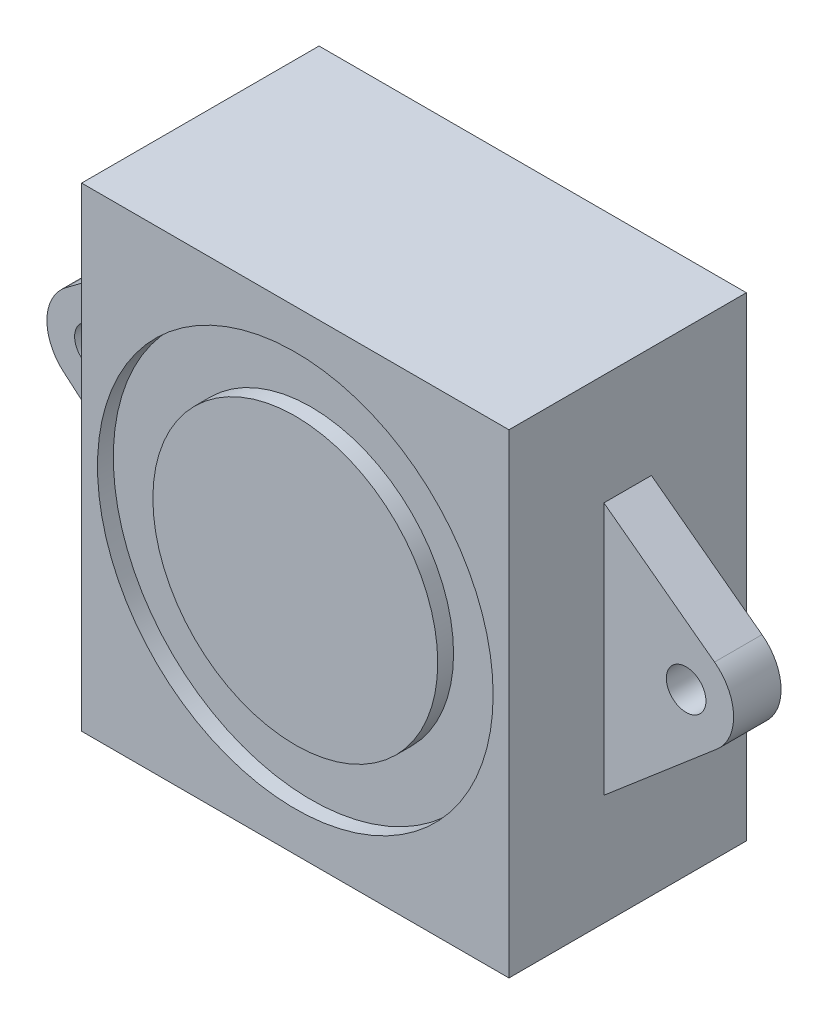
SolidWorks part; units mm, degrees
material "ABS"
ref_plane "Front Plane" through (0, 0, 0) normal (0, 0, 1) x (1, 0, 0)
ref_plane "Top Plane" through (0, 0, 0) normal (0, 1, 0) x (1, 0, 0)
ref_plane "Right Plane" through (0, 0, 0) normal (1, 0, 0) x (0, 0, -1)
sketch "Sketch1" plane through (0, 0, 0) normal (0, 0, 1) x (1, 0, 0)
  line L1 (0, 0) -> (27, 0)
  line L2 (0, 0) -> (0, 30)
  line L3 (0, 30) -> (27, 30)
  line L4 (27, 0) -> (27, 30)
  dimension "D1" = 27
  dimension "D2" = 30
extrude "Boss-Extrude1" add sketch "Sketch1" along normal blind 15
sketch "Sketch2" plane through (0, 0, 15) normal (0, 0, 1) x (1, 0, 0)
  circle A0 centre (13.5, 15) radius 9
  circle A1 centre (13.5, 15) radius 12.5
  dimension "D1" = 25
  dimension "D2" = 18
extrude "Cut-Extrude1" cut sketch "Sketch2" against normal blind 1
sketch "Sketch3" plane through (0, 0, 15) normal (0, 0, 1) x (1, 0, 0)
  line L0 (13.5, 30) -> (13.5, 17.0254)
  line L1 (27, 30) -> (0, 30) construction
  line L2 (0, 23) -> (-6.9895, 17.7832)
  line L3 (0, 30) -> (0, 0) construction
  line L4 (-7.1428, 13.0973) -> (0, 7)
  line L5 (34.1428, 13.0973) -> (27, 7)
  line L6 (27, 23) -> (33.9895, 17.7832)
  arc A0 (-6.9895, 17.7832) -> (-7.1428, 13.0973) centre (-5.1951, 15.379) ccw
  circle A1 centre (-5.1951, 15.379) radius 1.25
  circle A2 centre (32.1951, 15.379) radius 1.25
  arc A3 (33.9895, 17.7832) -> (34.1428, 13.0973) centre (32.1951, 15.379) cw
  point P14 (-10, 15.5362)
  line M4 (0, 30) -> (0, 0)
  line M6 (27, 0) -> (27, 30)
  dimension "D4" = 3
  dimension "D5" = 2.5
  dimension "D1" = 7
  dimension "D2" = 7
  dimension "D3" = 10
extrude "Boss-Extrude2" add sketch "Sketch3" against normal blind 9 contours L2 A0 L4 A1 M4 | A3 L6 L5 A2 M6
sketch "Sketch4" plane through (0, 0, 15) normal (0, 0, 1) x (1, 0, 0)
  line L0 (0, 23) -> (-13.0685, 23)
  line L1 (-13.0685, 23) -> (-13.0685, 5.3283)
  line L2 (-13.0685, 5.3283) -> (0, 7)
  line L3 (0, 7) -> (0, 23)
  line L4 (27, 23) -> (27, 7)
  line L5 (27, 7) -> (37.7366, 7)
  line L6 (37.7366, 7) -> (37.7366, 23)
  line L7 (37.7366, 23) -> (27, 23)
extrude "Cut-Extrude2" cut sketch "Sketch4" against normal blind 6
